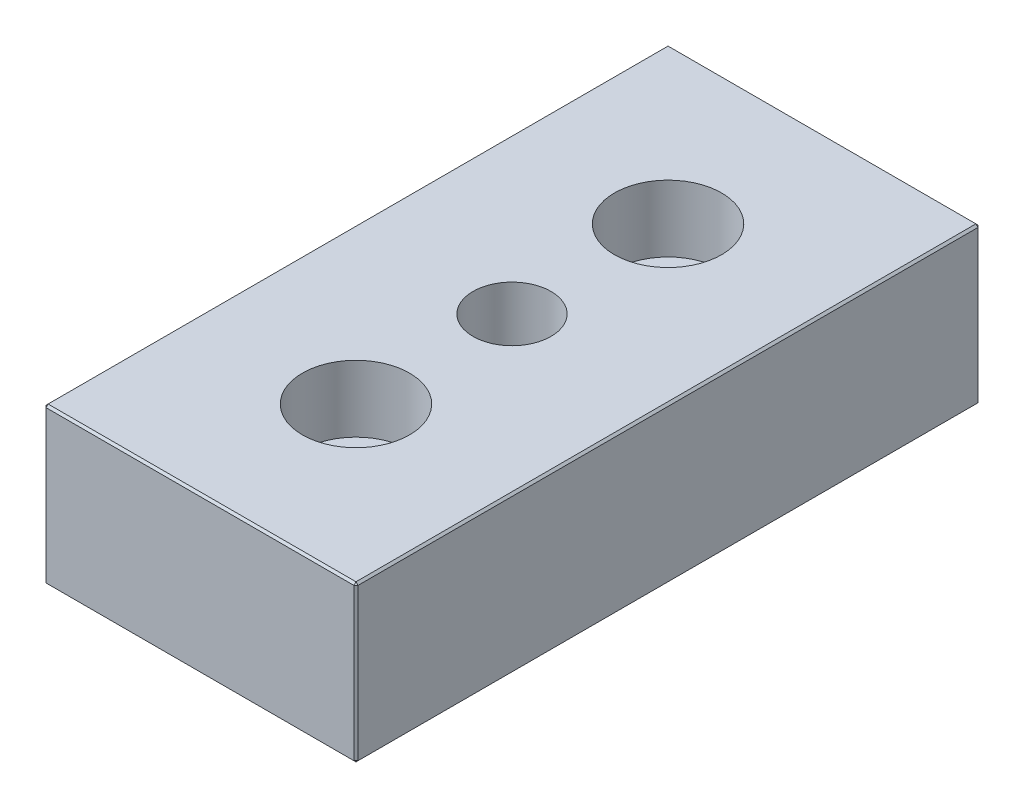
SolidWorks part; units mm, degrees
material "6105-T5 Aluminum"
ref_plane "Front Plane" through (0, 0, 0) normal (0, 0, 1) x (1, 0, 0)
ref_plane "Top Plane" through (0, 0, 0) normal (0, 1, 0) x (1, 0, 0)
ref_plane "Right Plane" through (0, 0, 0) normal (1, 0, 0) x (0, 0, -1)
sketch "Sketch1" plane through (0, 0, 0) normal (0, 1, 0) x (1, 0, 0)
  line L1 (-25.4, 76.2) -> (12.7, 76.2)
  line L2 (-25.4, 76.2) -> (-25.4, 0)
  line L3 (-25.4, 0) -> (12.7, 0)
  line L4 (12.7, 76.2) -> (12.7, 0)
  circle A0 centre (-6.35, 57.15) radius 4.1656
  circle A1 centre (-6.35, 19.05) radius 4.1656
  circle A2 centre (-6.35, 38.1) radius 4.7625
  dimension "D3" = 8.3312
  dimension "D1" = 38.1
  dimension "D2" = 76.2
extrude "Extrude1" add sketch "Sketch1" along normal blind 19.05
sketch "Sketch2" plane through (0, 19.05, 0) normal (0, 1, 0) x (1, 0, 0)
  circle A0 centre (-6.35, 57.15) radius 6.5405
  circle A1 centre (-6.35, 19.05) radius 6.5405
extrude "Cut-Extrude1" cut sketch "Sketch2" against normal blind 8.128
chamfer "Chamfer1" distance 0.254 angle 45 12 edges at (-25.4, 19.05, -38.1) (-25.4, 0, -38.1) (-6.35, 19.05, -76.2) (-25.4, 9.525, -76.2) (-6.35, 0, -76.2) (12.7, 19.05, -38.1) (12.7, 9.525, -76.2) (12.7, 0, -38.1) (-25.4, 9.525, 0) (-6.35, 19.05, 0) (12.7, 9.525, 0) (-6.35, 0, 0)
